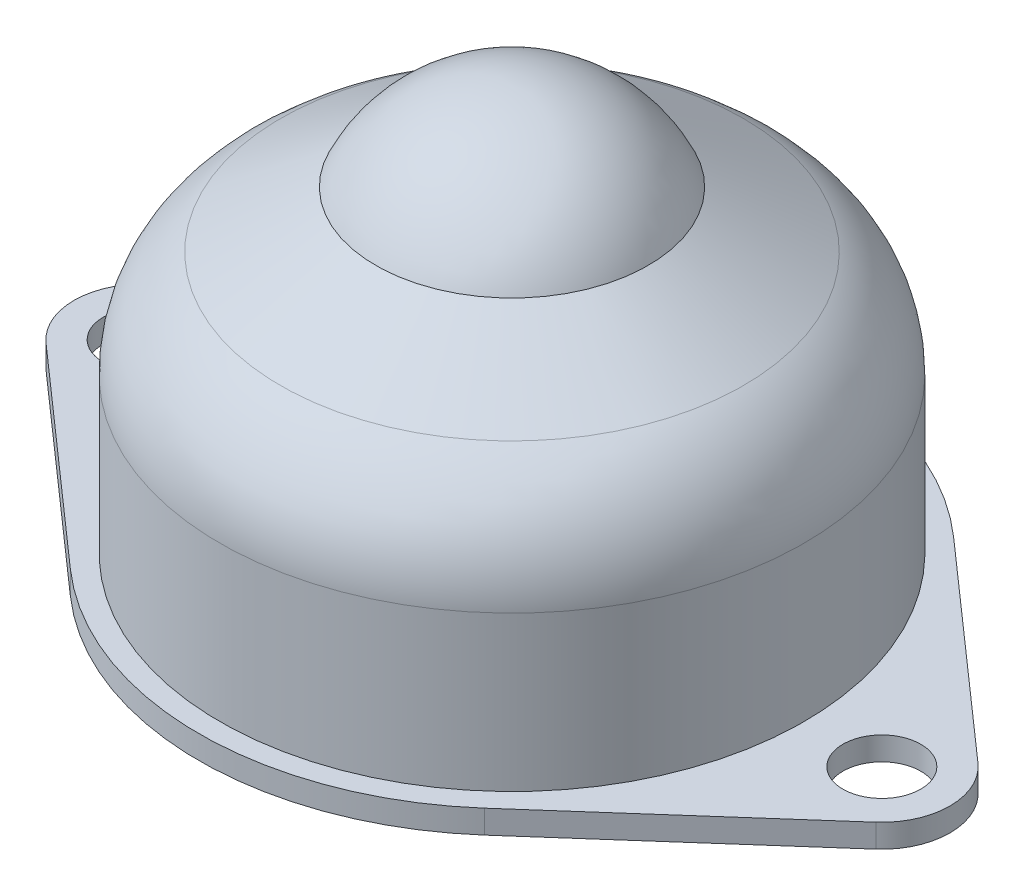
SolidWorks part; units mm, degrees
ref_plane "Front Plane" through (0, 0, 0) normal (0, 0, 1) x (1, 0, 0)
ref_plane "Top Plane" through (0, 0, 0) normal (0, 1, 0) x (1, 0, 0)
ref_plane "Right Plane" through (0, 0, 0) normal (1, 0, 0) x (0, 0, -1)
sketch "Sketch1" plane through (0, 0, 0) normal (0, 1, 0) x (1, 0, 0)
  line L0 (-21.3164, 2.6238) -> (-10.6391, 12.0505)
  line L1 (10.6391, 12.0505) -> (21.3164, 2.6238)
  line L2 (10.6391, -12.0505) -> (21.3164, -2.6238)
  line L3 (-21.3164, -2.6238) -> (-10.6391, -12.0505)
  line L4 (-19, 0) -> (19, 0) construction
  circle A0 centre (0, 0) radius 16.075
  circle A1 centre (19, 0) radius 3.5
  circle A2 centre (19, 0) radius 2
  circle A3 centre (-19, 0) radius 3.5
  circle A4 centre (-19, 0) radius 2
  point P17 (0, 0)
  point P18 (0, 0)
  point P19 (0, 0)
  dimension "D1" = 4
  dimension "D2" = 32.15
  dimension "D4" = 7
  dimension "D3" = 38
extrude "Boss-Extrude1" add sketch "Sketch1" along normal blind 1.2
sketch "Sketch3" plane through (0, 0, 0) normal (0, 0, 1) x (1, 0, 0)
  line L0 (-15, 1.2) -> (-15, 9.1375)
  line L1 (-21.3164, 1.2) -> (-10.6391, 1.2) construction
  line L2 (-11.8901, 14.5986) -> (-7, 17.5)
  line L3 (-15, 1.2) -> (0, 1.2)
  line L4 (10.6391, 1.2) -> (-10.6391, 1.2) construction
  line L5 (0, 1.2) -> (0, 22)
  arc A0 (-15, 9.1375) -> (-11.8901, 14.5986) centre (-8.65, 9.1375) cw
  arc A1 (-7, 17.5) -> (0, 22) centre (0, 14.3056) cw
  point P9 (0, 0)
  point P10 (0, 0)
  point P11 (-7, 18.6294)
  point P16 (0, 0)
  dimension "D5" = 6.35
  dimension "D1" = 22
  dimension "D2" = 15
  dimension "D3" = 7
  dimension "D4" = 4.5
  dimension "D6" = 7.9375
revolve "Revolve1" add sketch "Sketch3" angle 360 about L5
